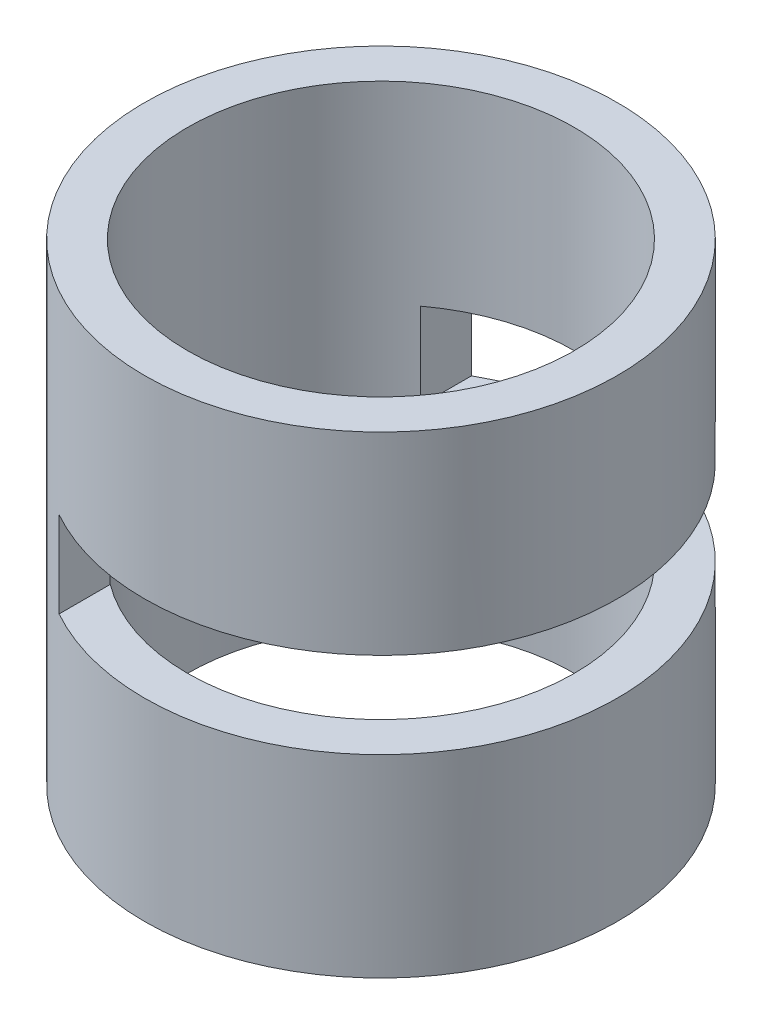
SolidWorks part; units mm, degrees
ref_plane "前视基准面" through (0, 0, 0) normal (0, 0, 1) x (1, 0, 0)
ref_plane "上视基准面" through (0, 0, 0) normal (0, 1, 0) x (1, 0, 0)
ref_plane "右视基准面" through (0, 0, 0) normal (1, 0, 0) x (0, 0, -1)
other "Configuration Table"
sketch "草图1" plane through (0, 0, 0) normal (0, 1, 0) x (1, 0, 0)
  circle A0 centre (0, 0) radius 9
  circle A1 centre (0, 0) radius 11
  dimension "D1" = 18
  dimension "D2" = 22
extrude "凸台-拉伸1" add sketch "草图1" along normal blind 22
sketch "草图2" plane through (0, 0, 0) normal (0, 0, 1) x (1, 0, 0)
  line L0 (0, 22.455) -> (0, -1.4218) construction
  line L1 (-5.38, 9) -> (13.3809, 9)
  line L2 (-5.38, 13) -> (13.3809, 13)
  line L3 (-5.38, 13) -> (-5.38, 9)
  line L4 (13.3809, 13) -> (13.3809, 9)
  dimension "D1" = 9
  dimension "D2" = 4
  dimension "D3" = 5.38
  dimension "D4" = 5.38
extrude "切除-拉伸2" cut sketch "草图2" against normal through all both and the other way through all contours L2 L4 L1 L3
